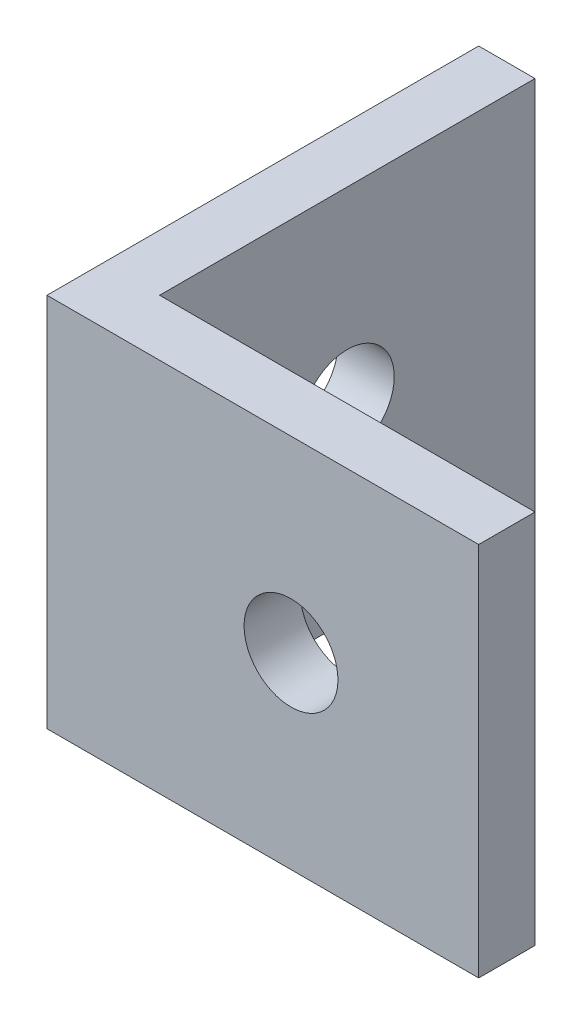
SolidWorks part; units mm, degrees
material "1060 Alloy"
ref_plane "Front Plane" through (0, 0, 0) normal (0, 0, 1) x (1, 0, 0)
ref_plane "Top Plane" through (0, 0, 0) normal (0, 1, 0) x (1, 0, 0)
ref_plane "Right Plane" through (0, 0, 0) normal (1, 0, 0) x (0, 0, -1)
sketch "Sketch1" plane through (0, 0, 0) normal (1, 0, 0) x (0, 0, -1)
  line L1 (-11.5, 10) -> (11.5, 10)
  line L2 (-11.5, 10) -> (-11.5, -10)
  line L3 (-11.5, -10) -> (11.5, -10)
  line L4 (11.5, 10) -> (11.5, -10)
  line L5 (-11.5, 10) -> (11.5, -10) construction
  line L6 (-11.5, -10) -> (11.5, 10) construction
  point P0 (0, 0)
  dimension "D1" = 20
  dimension "D2" = 23
extrude "Boss-Extrude1" add sketch "Sketch1" along normal blind 3
sketch "Sketch2" plane through (3, 0, 0) normal (1, 0, 0) x (0, 0, -1)
  line L0 (-11.5, -10) -> (11.5, -10) construction
  line L1 (-11.5, 10) -> (-8.5, 10)
  line L2 (-11.5, 10) -> (-11.5, -10)
  line L3 (-11.5, -10) -> (-8.5, -10)
  line L4 (-8.5, 10) -> (-8.5, -10)
  dimension "D1" = 3
extrude "Boss-Extrude2" add sketch "Sketch2" along normal blind 20
sketch "Sketch3" plane through (3, 0, 0) normal (1, 0, 0) x (0, 0, -1)
  line L2 (11.5, -10) -> (11.5, 10) construction
  line L3 (11.5, 10) -> (-8.5, 10) construction
  circle A0 centre (1.5, 0) radius 2.5
  point P3 (0, 0)
  dimension "D1" = 5
  dimension "D2" = 10
  dimension "D3" = 10
extrude "Cut-Extrude1" cut sketch "Sketch3" against normal up to next
sketch "Sketch4" plane through (0, 0, 8.5) normal (0, 0, -1) x (-1, 0, 0)
  line L0 (-23, -10) -> (-23, 10) construction
  line L3 (-23, -10) -> (-3, -10) construction
  circle A0 centre (-13, 0) radius 2.5
  dimension "D1" = 5
  dimension "D2" = 10
  dimension "D3" = 10
extrude "Cut-Extrude2" cut sketch "Sketch4" against normal up to next
